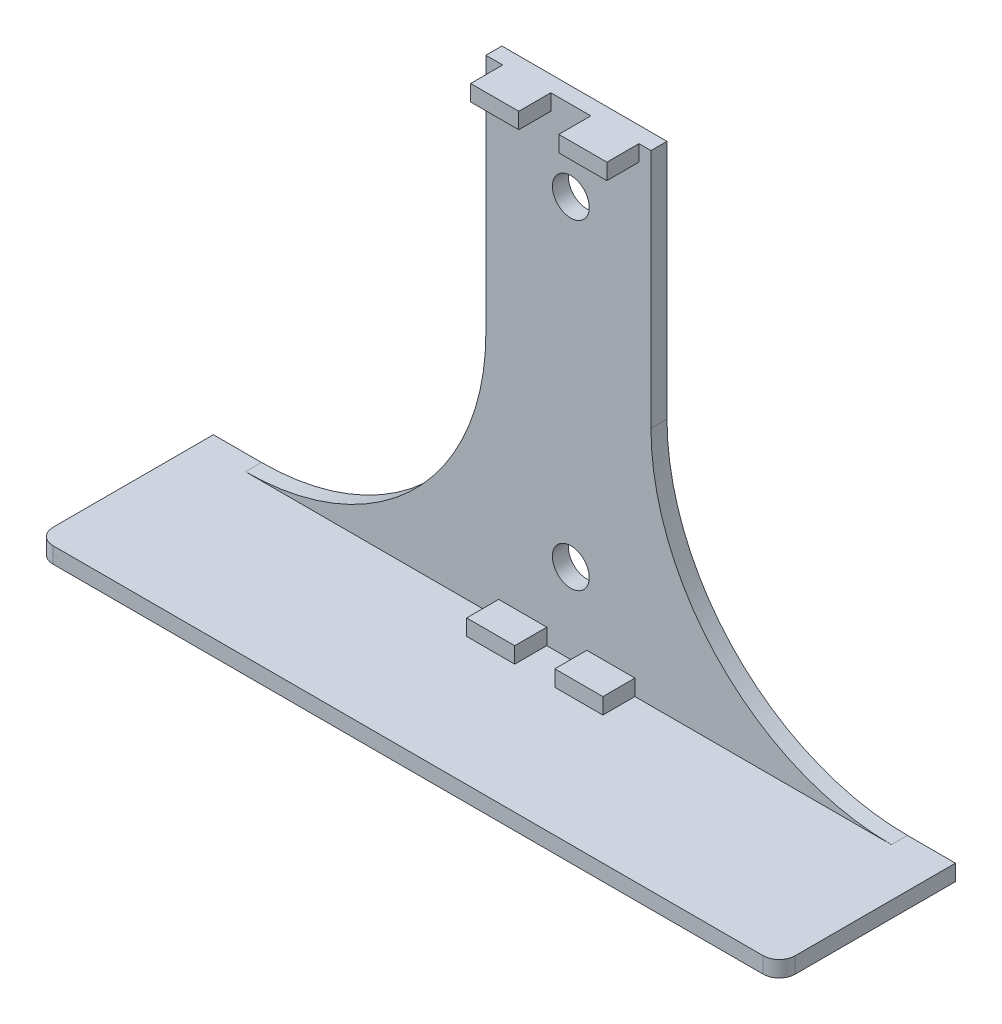
SolidWorks part; units mm, degrees
ref_plane "Front Plane" through (0, 0, 0) normal (0, 0, 1) x (1, 0, 0)
ref_plane "Top Plane" through (0, 0, 0) normal (0, 1, 0) x (1, 0, 0)
ref_plane "Right Plane" through (0, 0, 0) normal (1, 0, 0) x (0, 0, -1)
sketch "Sketch1" plane through (0, 0, 0) normal (0, 1, 0) x (1, 0, 0)
  line L9 (-192.6465, 84.5666) -> (-100.0465, 84.5666)
  line L10 (-192.6465, 84.5666) -> (-192.6465, 62.5666)
  line L11 (-192.6465, 62.5666) -> (-100.0465, 62.5666)
  line L12 (-100.0465, 84.5666) -> (-100.0465, 62.5666)
  line L13 (-192.6465, 84.5666) -> (-100.0465, 62.5666) construction
  line L14 (-192.6465, 62.5666) -> (-100.0465, 84.5666) construction
  point P0 (-146.3465, 73.5666)
  dimension "D1" = 92.6
  dimension "D2" = 22
extrude "Boss-Extrude1" add sketch "Sketch1" along normal blind 2
fillet "Fillet1" radius 2 2 edges at (-100.0465, 1, -62.5666) (-192.6465, 1, -62.5666)
sketch "Sketch5" plane through (0, 2, 0) normal (0, 1, 0) x (1, 0, 0)
  line L0 (-100.0465, 84.5666) -> (-192.6465, 84.5666) construction
  line L1 (-156.6465, 84.5666) -> (-136.0465, 84.5666)
  line L2 (-156.6465, 84.5666) -> (-156.6465, 82.5666)
  line L3 (-156.6465, 82.5666) -> (-136.0465, 82.5666)
  line L4 (-136.0465, 84.5666) -> (-136.0465, 82.5666)
  line L5 (-100.0465, 64.5666) -> (-100.0465, 84.5666) construction
  line L6 (-192.6465, 84.5666) -> (-192.6465, 64.5666) construction
  dimension "D1" = 36
  dimension "D2" = 36
  dimension "D3" = 2
extrude "Boss-Extrude3" add sketch "Sketch5" along normal blind 60
sketch "Sketch6" plane through (0, 0, -82.5666) normal (0, 0, 1) x (1, 0, 0)
  line L1 (-156.6465, 62) -> (-136.0465, 62) construction
  line L4 (-154.5465, 62) -> (-148.5465, 62)
  line L5 (-154.5465, 62) -> (-154.5465, 60)
  line L6 (-154.5465, 60) -> (-148.5465, 60)
  line L7 (-148.5465, 62) -> (-148.5465, 60)
  line L9 (-143.5465, 62) -> (-137.5465, 62)
  line L10 (-143.5465, 62) -> (-143.5465, 60)
  line L11 (-143.5465, 60) -> (-137.5465, 60)
  line L12 (-137.5465, 62) -> (-137.5465, 60)
  line L13 (-155.0465, 4) -> (-149.0465, 4)
  line L14 (-155.0465, 4) -> (-155.0465, 2)
  line L15 (-155.0465, 2) -> (-149.0465, 2)
  line L16 (-149.0465, 4) -> (-149.0465, 2)
  line L17 (-144.0465, 4) -> (-138.0465, 4)
  line L18 (-144.0465, 4) -> (-144.0465, 2)
  line L19 (-144.0465, 2) -> (-138.0465, 2)
  line L20 (-138.0465, 4) -> (-138.0465, 2)
  line L21 (-136.0465, 62) -> (-136.0465, 2) construction
  line L22 (-156.6465, 2) -> (-136.0465, 2) construction
  dimension "D3" = 6
  dimension "D4" = 5
  dimension "D2" = 6
  dimension "D5" = 2
  dimension "D6" = 0
  dimension "D7" = 6
  dimension "D8" = 6
  dimension "D10" = 5
  dimension "D11" = 2
  dimension "D12" = 2
extrude "Boss-Extrude4" add sketch "Sketch6" along normal blind 4
sketch "Sketch7" plane through (0, 0, -82.5666) normal (0, 0, 1) x (1, 0, 0)
  line L0 (-136.0465, 62) -> (-136.0465, 2) construction
  line L1 (-156.6465, 2) -> (-155.0465, 2) construction
  line L2 (-148.5465, 62) -> (-143.5465, 62) construction
  circle A0 centre (-146.0465, 52) radius 2.3
  circle A1 centre (-146.0465, 12) radius 2.3
  dimension "D1" = 4.6
  dimension "D2" = 4.6
  dimension "D3" = 10
  dimension "D4" = 10
  dimension "D5" = 10
  dimension "D6" = 10
extrude "Cut-Extrude1" cut sketch "Sketch7" against normal up to surface (2 mm away) up to face at (-146.3465, 16.5, -84.5666)
fillet "Fillet4" radius 30 2 edges at (-136.0465, 2, -83.5666) (-156.6465, 2, -83.5666)
equation "\"1.5.00mm\"=10"
